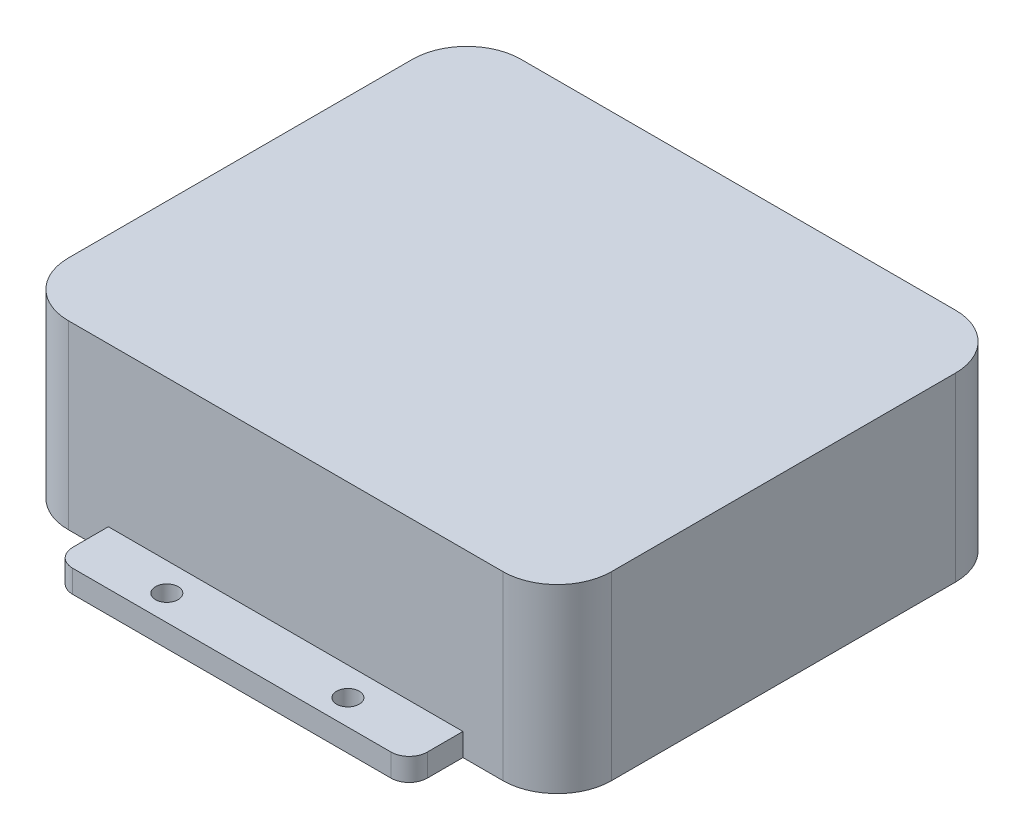
SolidWorks part; units mm, degrees
ref_plane "Front Plane" through (0, 0, 0) normal (0, 0, 1) x (1, 0, 0)
ref_plane "Top Plane" through (0, 0, 0) normal (0, 1, 0) x (1, 0, 0)
ref_plane "Right Plane" through (0, 0, 0) normal (1, 0, 0) x (0, 0, -1)
sketch "Sketch1" plane through (0, 0, 0) normal (0, 1, 0) x (1, 0, 0)
  line L1 (-30.48, -31.75) -> (30.48, -31.75)
  line L2 (-38.1, -24.13) -> (-38.1, 24.13)
  line L3 (-30.48, 31.75) -> (30.48, 31.75)
  line L4 (38.1, -24.13) -> (38.1, 24.13)
  line L5 (-38.1, -31.75) -> (38.1, 31.75) construction
  line L6 (-38.1, 31.75) -> (38.1, -31.75) construction
  arc A0 (-38.1, 24.13) -> (-30.48, 31.75) centre (-30.48, 24.13) cw
  arc A1 (-30.48, -31.75) -> (-38.1, -24.13) centre (-30.48, -24.13) cw
  arc A2 (30.48, -31.75) -> (38.1, -24.13) centre (30.48, -24.13) ccw
  arc A3 (30.48, 31.75) -> (38.1, 24.13) centre (30.48, 24.13) cw
  point P0 (0, 0)
  dimension "D3" = 7.62
  dimension "D4" = 7.62
  dimension "D1" = 63.5
  dimension "D2" = 76.2
extrude "Boss-Extrude1" add sketch "Sketch1" along normal blind 25.4 contours A3 L3 A0 L2 A1 L1 A2 L4
sketch "Sketch2" plane through (0, 0, 0) normal (0, 1, 0) x (1, 0, 0)
  line L0 (-13.97, 0) -> (13.97, 0) construction
  line L1 (0, -13.97) -> (0, 13.97) construction
  line L2 (-24.8695, -31.75) -> (24.8695, -31.75)
  line L4 (-22.3295, -39.2949) -> (22.3295, -39.2949)
  line L5 (24.8695, -31.75) -> (24.8695, -36.7549)
  line L6 (-24.8695, -31.75) -> (-24.8695, -36.7549)
  line L7 (-24.8695, 31.75) -> (-24.8695, 36.7549)
  line L8 (-22.3295, 39.2949) -> (22.3295, 39.2949)
  line L9 (24.8695, 31.75) -> (24.8695, 36.7549)
  line L10 (-24.8695, 31.75) -> (24.8695, 31.75)
  circle A0 centre (12.7, -35.7188) radius 1.5875
  circle A1 centre (-12.7, -35.7188) radius 1.5875
  arc A2 (24.8695, -36.7549) -> (22.3295, -39.2949) centre (22.3295, -36.7549) cw
  arc A3 (-22.3295, -39.2949) -> (-24.8695, -36.7549) centre (-22.3295, -36.7549) cw
  circle A4 centre (12.7, 35.7188) radius 1.5875
  circle A5 centre (-12.7, 35.7188) radius 1.5875
  arc A6 (-22.3295, 39.2949) -> (-24.8695, 36.7549) centre (-22.3295, 36.7549) ccw
  arc A7 (24.8695, 36.7549) -> (22.3295, 39.2949) centre (22.3295, 36.7549) ccw
  point P11 (24.8695, -39.2949)
  point P16 (-24.8695, -39.2949)
  dimension "D3" = 3.175
  dimension "D4" = 2.54
  dimension "D1" = 35.7188
  dimension "D2" = 12.7
extrude "Boss-Extrude2" add sketch "Sketch2" along normal blind 3.175
